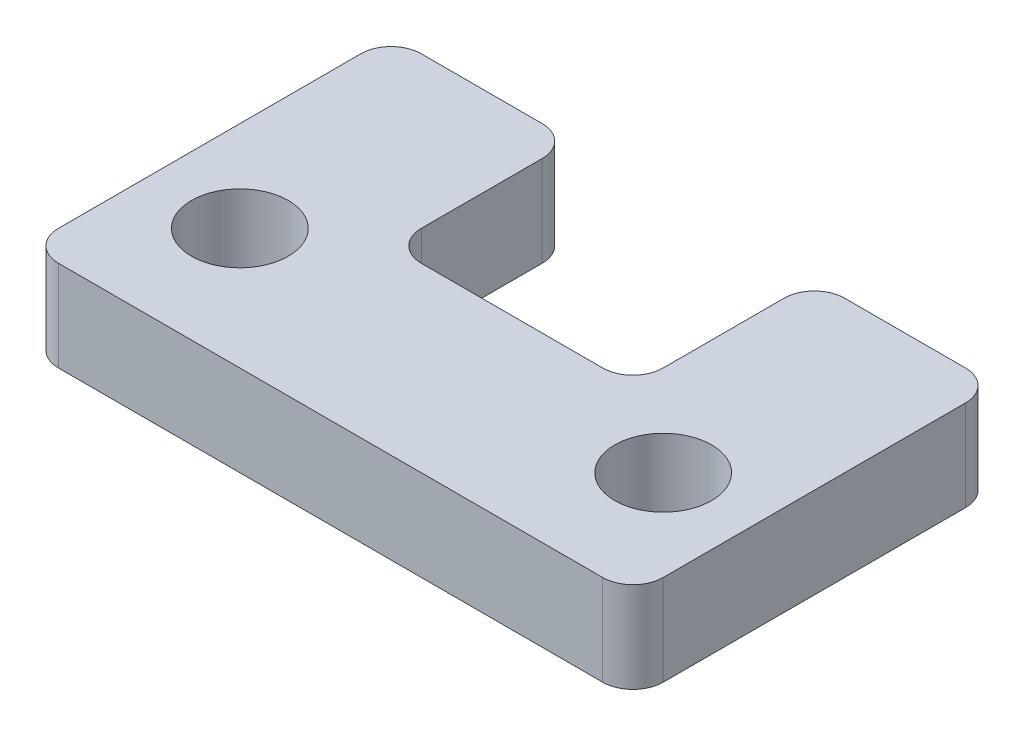
SolidWorks part; units mm, degrees
material "碳板"
ref_plane "前视基准面" through (0, 0, 0) normal (0, 0, 1) x (1, 0, 0)
ref_plane "上视基准面" through (0, 0, 0) normal (0, 1, 0) x (1, 0, 0)
ref_plane "右视基准面" through (0, 0, 0) normal (1, 0, 0) x (0, 0, -1)
sketch "草图1" plane through (0, 0, 0) normal (0, 1, 0) x (1, 0, 0)
  line L0 (0, 26.9081) -> (0, -22.2285) construction
  line L1 (-32.8332, 0) -> (32.2294, 0) construction
  line L2 (-10, 0) -> (10, 0)
  line L3 (10, 0) -> (10, 12)
  line L4 (10, 12) -> (4, 12)
  line L5 (4, 12) -> (4, 6)
  line L6 (4, 6) -> (-4, 6)
  line L7 (-10, 0) -> (-10, 12)
  line L8 (-10, 12) -> (-4, 12)
  line L9 (-4, 12) -> (-4, 6)
  circle A0 centre (7, 4) radius 1.6
  circle A1 centre (-7, 4) radius 1.6
  point P7 (7, 1.8687)
  point P14 (0, 0)
  point P19 (0, 6)
  dimension "D1" = 14
  dimension "D3" = 3.2
  dimension "D2" = 20
  dimension "D4" = 4
  dimension "D5" = 12
  dimension "D6" = 8
  dimension "D7" = 6
extrude "凸台-拉伸1" add sketch "草图1" along normal blind 3
fillet "圆角1" radius 1 8 edges at (-4, 1.5, -12) (-4, 1.5, -6) (4, 1.5, -6) (4, 1.5, -12) (10, 1.5, -12) (-10, 1.5, 0) (-10, 1.5, -12) (10, 1.5, 0)
